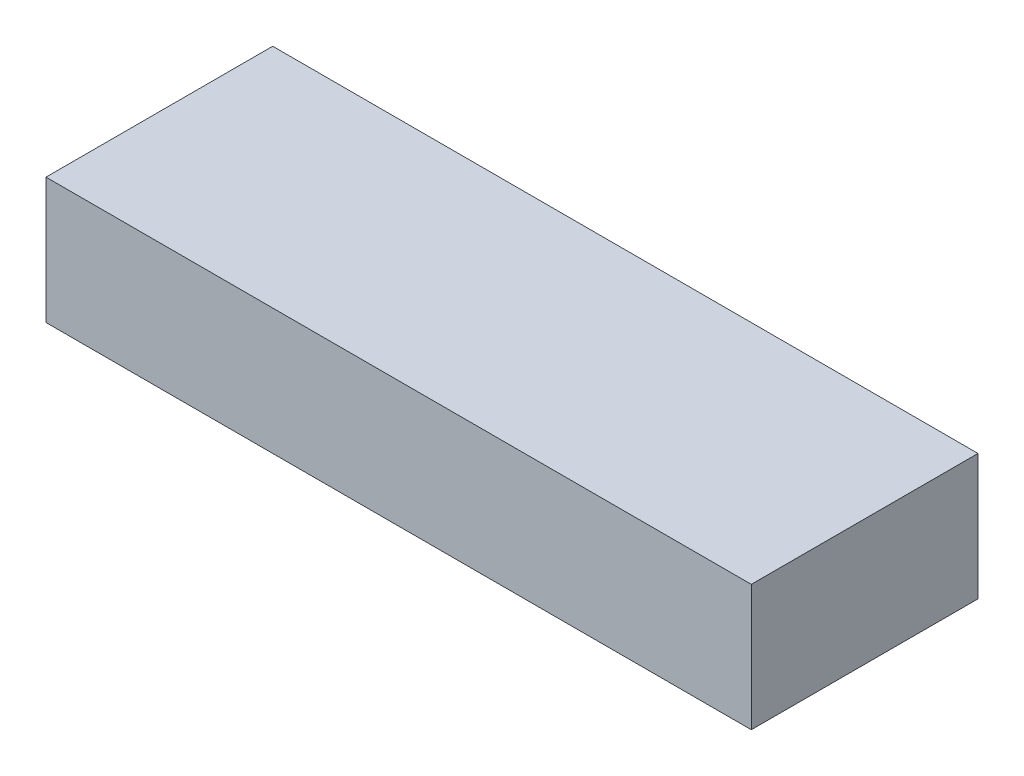
SolidWorks part; units mm, degrees
ref_plane "Plano frontal" through (0, 0, 0) normal (0, 0, 1) x (1, 0, 0)
ref_plane "Plano superior" through (0, 0, 0) normal (0, 1, 0) x (1, 0, 0)
ref_plane "Plano direito" through (0, 0, 0) normal (1, 0, 0) x (0, 0, -1)
sketch "Esboço1" plane through (0, 0, 0) normal (0, 1, 0) x (1, 0, 0)
  line L1 (70, -22.5) -> (-70, -22.5)
  line L2 (70, -22.5) -> (70, 22.5)
  line L3 (70, 22.5) -> (-70, 22.5)
  line L4 (-70, -22.5) -> (-70, 22.5)
  line L5 (70, -22.5) -> (-70, 22.5) construction
  line L6 (70, 22.5) -> (-70, -22.5) construction
  point P0 (0, 0)
  dimension "D1" = 140
  dimension "D2" = 45
extrude "Ressalto-extrusão1" add sketch "Esboço1" along normal blind 25
